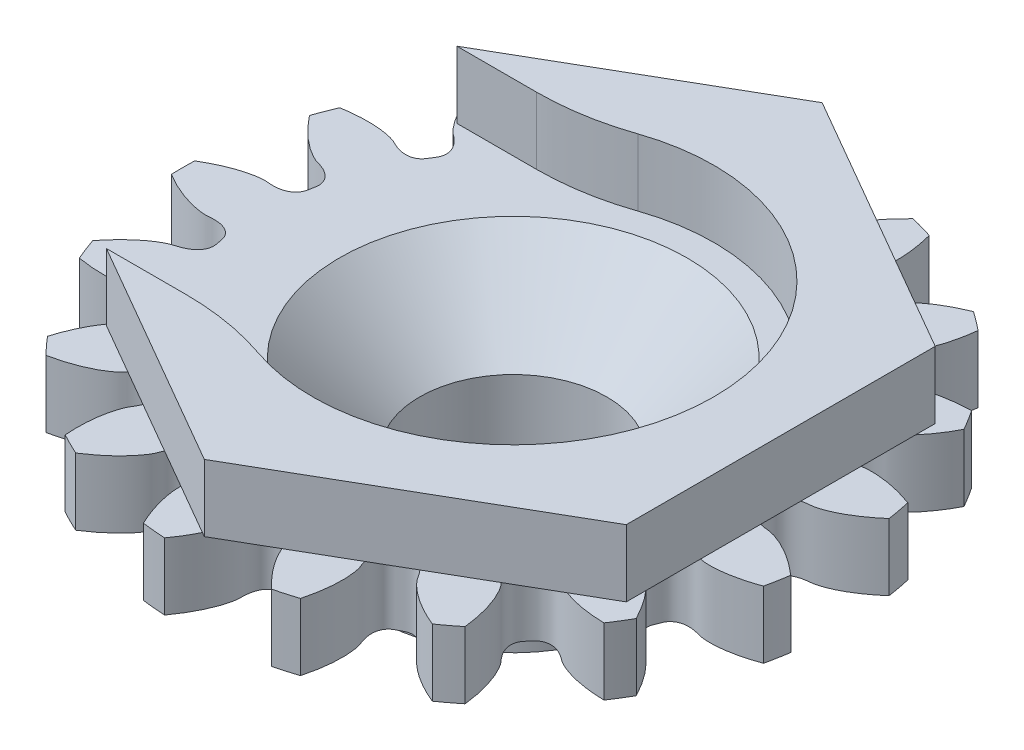
SolidWorks part; units mm, degrees
material "ABS"
ref_plane "前视基准面" through (0, 0, 0) normal (0, 0, 1) x (1, 0, 0)
ref_plane "上视基准面" through (0, 0, 0) normal (0, 1, 0) x (1, 0, 0)
ref_plane "右视基准面" through (0, 0, 0) normal (1, 0, 0) x (0, 0, -1)
sketch "草图1" plane through (0, 0, 0) normal (0, 1, 0) x (1, 0, 0)
  arc A0 (14.1766, -20.2266) -> (15.5749, -19.1706) centre (0, 0) ccw
  arc A1 (20.5259, -13.7396) -> (21.4484, -12.2498) centre (0, 0) ccw
  arc A2 (24.1032, -5.397) -> (24.4251, -3.6746) centre (0, 0) ccw
  arc A3 (24.4251, 3.6746) -> (24.1032, 5.397) centre (0, 0) ccw
  arc A4 (21.4484, 12.2498) -> (20.5259, 13.7396) centre (0, 0) ccw
  arc A5 (15.5749, 19.1706) -> (14.1766, 20.2266) centre (0, 0) ccw
  arc A6 (7.5979, 23.5024) -> (5.9126, 23.9819) centre (0, 0) ccw
  arc A7 (-1.4052, 24.66) -> (-3.15, 24.4983) centre (0, 0) ccw
  arc A8 (-10.2185, 22.4871) -> (-11.7871, 21.7061) centre (0, 0) ccw
  arc A9 (-17.6518, 17.2773) -> (-18.8323, 15.9824) centre (0, 0) ccw
  arc A10 (-22.7011, 9.734) -> (-23.3341, 8.1001) centre (0, 0) ccw
  arc A11 (-24.6845, 0.8761) -> (-24.6845, -0.8761) centre (0, 0) ccw
  arc A12 (-23.3341, -8.1001) -> (-22.7011, -9.734) centre (0, 0) ccw
  arc A13 (-18.8323, -15.9824) -> (-17.6518, -17.2773) centre (0, 0) ccw
  arc A14 (-11.7871, -21.7061) -> (-10.2185, -22.4871) centre (0, 0) ccw
  arc A15 (-3.15, -24.4983) -> (-1.4052, -24.66) centre (0, 0) ccw
  arc A16 (5.9126, -23.9819) -> (7.5979, -23.5024) centre (0, 0) ccw
  spline S0 degree 3 poles (7.5979, -23.5024) (7.6571, -23.2793) (7.7407, -22.9281) (7.8317, -22.4531) (7.8892, -22.0896) (7.9319, -21.7465) (7.9614, -21.4245) (7.979, -21.1239) (7.9861, -20.8452) (7.9844, -20.5887) (7.9751, -20.3547) (7.9598, -20.1434) (7.9399, -19.9548) (7.9169, -19.7891) (7.8924, -19.6462) (7.8677, -19.5261) (7.8443, -19.4285) (7.8237, -19.3532) (7.7717, -19.1857) (7.6897, -19.0075) (7.6268, -18.795) (7.5931, -18.6651) (7.5663, -18.537) (7.5463, -18.4107) (7.5333, -18.2857) (7.5277, -18.1616) (7.5302, -18.0377) (7.5415, -17.9135) (7.5631, -17.7881) (7.597, -17.6612) (7.6456, -17.5329) (7.7122, -17.4041) (7.7999, -17.2778) (7.9111, -17.1586) (8.0352, -17.0633) (8.2001, -16.9672) (8.4041, -16.8777) (8.5985, -16.7688) (8.7745, -16.6951) (8.9254, -16.6536) (9.0875, -16.6367) (9.2412, -16.6428) (9.384, -16.6673) (9.5158, -16.7058) (9.6374, -16.7552) (9.7505, -16.8135) (9.8565, -16.8794) (9.9568, -16.9521) (10.0525, -17.0313) (10.1444, -17.117) (10.2331, -17.2091) (10.3192, -17.3076) (10.4026, -17.4129) (10.5343, -17.5911) (10.627, -17.764) (10.7294, -17.9063) (10.777, -17.9681) (10.8408, -18.0456) (10.9218, -18.1378) (11.021, -18.2435) (11.1394, -18.3616) (11.2779, -18.4911) (11.4373, -18.6307) (11.6185, -18.7791) (11.8221, -18.9351) (12.0488, -19.0973) (12.2993, -19.2644) (12.5741, -19.435) (12.8736, -19.6076) (13.1983, -19.7809) (13.6322, -19.9944) (13.9629, -20.1394) (14.1766, -20.2266) knots 0.010677 0.010677 0.010677 0.010677 0.058365 0.085243 0.110586 0.134392 0.156663 0.177398 0.196597 0.21426 0.230387 0.244978 0.258033 0.269552 0.279536 0.287983 0.294895 0.300271 0.30411 0.331114 0.340625 0.349862 0.358855 0.367643 0.376273 0.384801 0.3933 0.401854 0.410565 0.419553 0.428946 0.438871 0.449424 0.460632 0.472413 0.481614 0.5 0.518386 0.527587 0.539368 0.550576 0.561129 0.571054 0.580447 0.589435 0.598146 0.6067 0.615199 0.623727 0.632357 0.641145 0.650138 0.659375 0.668886 0.69589 0.699729 0.705105 0.712017 0.720464 0.730448 0.741967 0.755022 0.769613 0.78574 0.803403 0.822602 0.843337 0.865608 0.889414 0.914757 0.941635 0.989323 0.989323 0.989323 0.989323
  spline S1 degree 3 poles (15.5749, -19.1706) (15.5495, -18.9412) (15.5005, -18.5835) (15.4139, -18.1078) (15.3361, -17.7481) (15.252, -17.4127) (15.1632, -17.1018) (15.071, -16.8151) (14.977, -16.5526) (14.8827, -16.3141) (14.7895, -16.0992) (14.6989, -15.9077) (14.6122, -15.7391) (14.531, -15.5929) (14.4565, -15.4685) (14.39, -15.3654) (14.3329, -15.2828) (14.2865, -15.2201) (14.1776, -15.0827) (14.0367, -14.9461) (13.9014, -14.7707) (13.8229, -14.6617) (13.7517, -14.552) (13.6874, -14.4414) (13.6302, -14.3296) (13.5801, -14.2159) (13.5377, -14.0995) (13.5033, -13.9795) (13.4782, -13.8548) (13.464, -13.7243) (13.4629, -13.587) (13.4785, -13.4429) (13.5147, -13.2934) (13.5753, -13.1421) (13.6566, -13.0084) (13.7756, -12.8592) (13.9335, -12.7021) (14.0754, -12.5303) (14.2129, -12.398) (14.3386, -12.3048) (14.4837, -12.2305) (14.6292, -12.1806) (14.7712, -12.1519) (14.908, -12.1402) (15.0393, -12.1424) (15.1658, -12.1559) (15.2884, -12.179) (15.4082, -12.2105) (15.5261, -12.2499) (15.6428, -12.2965) (15.7588, -12.3504) (15.8746, -12.4111) (15.9904, -12.4792) (16.1775, -12.5978) (16.3265, -12.7255) (16.4733, -12.8213) (16.5401, -12.8617) (16.6276, -12.9109) (16.7364, -12.9675) (16.8671, -13.0303) (17.0202, -13.0977) (17.1961, -13.1684) (17.3952, -13.241) (17.6177, -13.3139) (17.8639, -13.3858) (18.134, -13.4552) (18.4279, -13.5205) (18.7457, -13.5803) (19.0874, -13.6331) (19.4527, -13.6773) (19.9345, -13.7197) (20.2952, -13.7355) (20.5259, -13.7396) knots 0.010677 0.010677 0.010677 0.010677 0.058365 0.085243 0.110586 0.134392 0.156663 0.177398 0.196597 0.21426 0.230387 0.244978 0.258033 0.269552 0.279536 0.287983 0.294895 0.300271 0.30411 0.331114 0.340625 0.349862 0.358855 0.367643 0.376273 0.384801 0.3933 0.401854 0.410565 0.419553 0.428946 0.438871 0.449424 0.460632 0.472413 0.481614 0.5 0.518386 0.527587 0.539368 0.550576 0.561129 0.571054 0.580447 0.589435 0.598146 0.6067 0.615199 0.623727 0.632357 0.641145 0.650138 0.659375 0.668886 0.69589 0.699729 0.705105 0.712017 0.720464 0.730448 0.741967 0.755022 0.769613 0.78574 0.803403 0.822602 0.843337 0.865608 0.889414 0.914757 0.941635 0.989323 0.989323 0.989323 0.989323
  spline S2 degree 3 poles (21.4484, -12.2498) (21.3418, -12.0451) (21.167, -11.7292) (20.9143, -11.3169) (20.7118, -11.0095) (20.5123, -10.7272) (20.3171, -10.4693) (20.1276, -10.2354) (19.9451, -10.0245) (19.771, -9.8362) (19.6065, -9.6695) (19.4528, -9.5237) (19.3111, -9.3977) (19.1825, -9.2907) (19.0681, -9.2017) (18.9689, -9.1295) (18.8859, -9.0732) (18.8199, -9.0314) (18.6687, -8.9426) (18.488, -8.8662) (18.2984, -8.7515) (18.1859, -8.6782) (18.0799, -8.6016) (17.98, -8.5218) (17.8862, -8.4382) (17.7985, -8.3502) (17.7168, -8.257) (17.6415, -8.1575) (17.573, -8.0503) (17.5125, -7.9337) (17.462, -7.8061) (17.4244, -7.6661) (17.4042, -7.5137) (17.4061, -7.3507) (17.4335, -7.1966) (17.4906, -7.0146) (17.5811, -6.811) (17.6514, -6.5996) (17.7319, -6.4265) (17.8154, -6.2942) (17.9238, -6.1725) (18.0415, -6.0734) (18.1635, -5.9953) (18.2868, -5.935) (18.4101, -5.8896) (18.5329, -5.8565) (18.6556, -5.8337) (18.7787, -5.8199) (18.9028, -5.814) (19.0285, -5.8154) (19.1561, -5.8237) (19.286, -5.8385) (19.4186, -5.8601) (19.6359, -5.9031) (19.821, -5.9683) (19.9925, -6.0046) (20.0694, -6.0182) (20.1687, -6.0325) (20.2906, -6.046) (20.4352, -6.0573) (20.6023, -6.0648) (20.7919, -6.0672) (21.0037, -6.063) (21.2376, -6.0506) (21.4931, -6.0287) (21.77, -5.9959) (22.0677, -5.9506) (22.3856, -5.8915) (22.7233, -5.8173) (23.08, -5.7266) (23.5445, -5.5921) (23.8865, -5.4765) (24.1032, -5.397) knots 0.010677 0.010677 0.010677 0.010677 0.058365 0.085243 0.110586 0.134392 0.156663 0.177398 0.196597 0.21426 0.230387 0.244978 0.258033 0.269552 0.279536 0.287983 0.294895 0.300271 0.30411 0.331114 0.340625 0.349862 0.358855 0.367643 0.376273 0.384801 0.3933 0.401854 0.410565 0.419553 0.428946 0.438871 0.449424 0.460632 0.472413 0.481614 0.5 0.518386 0.527587 0.539368 0.550576 0.561129 0.571054 0.580447 0.589435 0.598146 0.6067 0.615199 0.623727 0.632357 0.641145 0.650138 0.659375 0.668886 0.69589 0.699729 0.705105 0.712017 0.720464 0.730448 0.741967 0.755022 0.769613 0.78574 0.803403 0.822602 0.843337 0.865608 0.889414 0.914757 0.941635 0.989323 0.989323 0.989323 0.989323
  spline S3 degree 3 poles (24.4251, -3.6746) (24.2518, -3.5221) (23.9747, -3.2908) (23.5901, -2.9975) (23.2903, -2.7841) (23.0023, -2.5929) (22.7271, -2.423) (22.4659, -2.2733) (22.2196, -2.1426) (21.9892, -2.0299) (21.7756, -1.9339) (21.5796, -1.8534) (21.4019, -1.7871) (21.2434, -1.7338) (21.1045, -1.6921) (20.986, -1.6607) (20.8882, -1.6381) (20.8116, -1.623) (20.6385, -1.5948) (20.4424, -1.5889) (20.2242, -1.5504) (20.0928, -1.5227) (19.9662, -1.4896) (19.8443, -1.4512) (19.7266, -1.4071) (19.613, -1.3568) (19.5032, -1.2994) (19.397, -1.2338) (19.2944, -1.1586) (19.1959, -1.0717) (19.1027, -0.971) (19.0171, -0.854) (18.9432, -0.7192) (18.8861, -0.5665) (18.856, -0.4129) (18.8435, -0.2225) (18.8543, 0) (18.8435, 0.2225) (18.856, 0.4129) (18.8861, 0.5665) (18.9432, 0.7192) (19.0171, 0.854) (19.1027, 0.971) (19.1959, 1.0717) (19.2944, 1.1586) (19.397, 1.2338) (19.5032, 1.2994) (19.613, 1.3568) (19.7266, 1.4071) (19.8443, 1.4512) (19.9662, 1.4896) (20.0928, 1.5227) (20.2242, 1.5504) (20.4424, 1.5889) (20.6385, 1.5948) (20.8116, 1.623) (20.8882, 1.6381) (20.986, 1.6607) (21.1045, 1.6921) (21.2434, 1.7338) (21.4019, 1.7871) (21.5796, 1.8534) (21.7756, 1.9339) (21.9892, 2.0299) (22.2196, 2.1426) (22.4659, 2.2733) (22.7271, 2.423) (23.0023, 2.5929) (23.2903, 2.7841) (23.5901, 2.9975) (23.9747, 3.2908) (24.2518, 3.5221) (24.4251, 3.6746) knots 0.010677 0.010677 0.010677 0.010677 0.058365 0.085243 0.110586 0.134392 0.156663 0.177398 0.196597 0.21426 0.230387 0.244978 0.258033 0.269552 0.279536 0.287983 0.294895 0.300271 0.30411 0.331114 0.340625 0.349862 0.358855 0.367643 0.376273 0.384801 0.3933 0.401854 0.410565 0.419553 0.428946 0.438871 0.449424 0.460632 0.472413 0.481614 0.5 0.518386 0.527587 0.539368 0.550576 0.561129 0.571054 0.580447 0.589435 0.598146 0.6067 0.615199 0.623727 0.632357 0.641145 0.650138 0.659375 0.668886 0.69589 0.699729 0.705105 0.712017 0.720464 0.730448 0.741967 0.755022 0.769613 0.78574 0.803403 0.822602 0.843337 0.865608 0.889414 0.914757 0.941635 0.989323 0.989323 0.989323 0.989323
  spline S4 degree 3 poles (24.1032, 5.397) (23.8865, 5.4765) (23.5445, 5.5921) (23.08, 5.7266) (22.7233, 5.8173) (22.3856, 5.8915) (22.0677, 5.9506) (21.77, 5.9959) (21.4931, 6.0287) (21.2376, 6.0506) (21.0037, 6.063) (20.7919, 6.0672) (20.6023, 6.0648) (20.4352, 6.0573) (20.2906, 6.046) (20.1687, 6.0325) (20.0694, 6.0182) (19.9925, 6.0046) (19.821, 5.9683) (19.6359, 5.9031) (19.4186, 5.8601) (19.286, 5.8385) (19.1561, 5.8237) (19.0285, 5.8154) (18.9028, 5.814) (18.7787, 5.8199) (18.6556, 5.8337) (18.5329, 5.8565) (18.4101, 5.8896) (18.2868, 5.935) (18.1635, 5.9953) (18.0415, 6.0734) (17.9238, 6.1725) (17.8154, 6.2942) (17.7319, 6.4265) (17.6514, 6.5996) (17.5811, 6.811) (17.4906, 7.0146) (17.4335, 7.1966) (17.4061, 7.3507) (17.4042, 7.5137) (17.4244, 7.6661) (17.462, 7.8061) (17.5125, 7.9337) (17.573, 8.0503) (17.6415, 8.1575) (17.7168, 8.257) (17.7985, 8.3502) (17.8862, 8.4382) (17.98, 8.5218) (18.0799, 8.6016) (18.1859, 8.6782) (18.2984, 8.7515) (18.488, 8.8662) (18.6687, 8.9426) (18.8199, 9.0314) (18.8859, 9.0732) (18.9689, 9.1295) (19.0681, 9.2017) (19.1825, 9.2907) (19.3111, 9.3977) (19.4528, 9.5237) (19.6065, 9.6695) (19.771, 9.8362) (19.9451, 10.0245) (20.1276, 10.2354) (20.3171, 10.4693) (20.5123, 10.7272) (20.7118, 11.0095) (20.9143, 11.3169) (21.167, 11.7292) (21.3418, 12.0451) (21.4484, 12.2498) knots 0.010677 0.010677 0.010677 0.010677 0.058365 0.085243 0.110586 0.134392 0.156663 0.177398 0.196597 0.21426 0.230387 0.244978 0.258033 0.269552 0.279536 0.287983 0.294895 0.300271 0.30411 0.331114 0.340625 0.349862 0.358855 0.367643 0.376273 0.384801 0.3933 0.401854 0.410565 0.419553 0.428946 0.438871 0.449424 0.460632 0.472413 0.481614 0.5 0.518386 0.527587 0.539368 0.550576 0.561129 0.571054 0.580447 0.589435 0.598146 0.6067 0.615199 0.623727 0.632357 0.641145 0.650138 0.659375 0.668886 0.69589 0.699729 0.705105 0.712017 0.720464 0.730448 0.741967 0.755022 0.769613 0.78574 0.803403 0.822602 0.843337 0.865608 0.889414 0.914757 0.941635 0.989323 0.989323 0.989323 0.989323
  spline S5 degree 3 poles (20.5259, 13.7396) (20.2952, 13.7355) (19.9345, 13.7197) (19.4527, 13.6773) (19.0874, 13.6331) (18.7457, 13.5803) (18.4279, 13.5205) (18.134, 13.4552) (17.8639, 13.3858) (17.6177, 13.3139) (17.3952, 13.241) (17.1961, 13.1684) (17.0202, 13.0977) (16.8671, 13.0303) (16.7364, 12.9675) (16.6276, 12.9109) (16.5401, 12.8617) (16.4733, 12.8213) (16.3265, 12.7255) (16.1775, 12.5978) (15.9904, 12.4792) (15.8746, 12.4111) (15.7588, 12.3504) (15.6428, 12.2965) (15.5261, 12.2499) (15.4082, 12.2105) (15.2884, 12.179) (15.1658, 12.1559) (15.0393, 12.1424) (14.908, 12.1402) (14.7712, 12.1519) (14.6292, 12.1806) (14.4837, 12.2305) (14.3386, 12.3048) (14.2129, 12.398) (14.0754, 12.5303) (13.9335, 12.7021) (13.7756, 12.8592) (13.6566, 13.0084) (13.5753, 13.1421) (13.5147, 13.2934) (13.4785, 13.4429) (13.4629, 13.587) (13.464, 13.7243) (13.4782, 13.8548) (13.5033, 13.9795) (13.5377, 14.0995) (13.5801, 14.2159) (13.6302, 14.3296) (13.6874, 14.4414) (13.7517, 14.552) (13.8229, 14.6617) (13.9014, 14.7707) (14.0367, 14.9461) (14.1776, 15.0827) (14.2865, 15.2201) (14.3329, 15.2828) (14.39, 15.3654) (14.4565, 15.4685) (14.531, 15.5929) (14.6122, 15.7391) (14.6989, 15.9077) (14.7895, 16.0992) (14.8827, 16.3141) (14.977, 16.5526) (15.071, 16.8151) (15.1632, 17.1018) (15.252, 17.4127) (15.3361, 17.7481) (15.4139, 18.1078) (15.5005, 18.5835) (15.5495, 18.9412) (15.5749, 19.1706) knots 0.010677 0.010677 0.010677 0.010677 0.058365 0.085243 0.110586 0.134392 0.156663 0.177398 0.196597 0.21426 0.230387 0.244978 0.258033 0.269552 0.279536 0.287983 0.294895 0.300271 0.30411 0.331114 0.340625 0.349862 0.358855 0.367643 0.376273 0.384801 0.3933 0.401854 0.410565 0.419553 0.428946 0.438871 0.449424 0.460632 0.472413 0.481614 0.5 0.518386 0.527587 0.539368 0.550576 0.561129 0.571054 0.580447 0.589435 0.598146 0.6067 0.615199 0.623727 0.632357 0.641145 0.650138 0.659375 0.668886 0.69589 0.699729 0.705105 0.712017 0.720464 0.730448 0.741967 0.755022 0.769613 0.78574 0.803403 0.822602 0.843337 0.865608 0.889414 0.914757 0.941635 0.989323 0.989323 0.989323 0.989323
  spline S6 degree 3 poles (14.1766, 20.2266) (13.9629, 20.1394) (13.6322, 19.9944) (13.1983, 19.7809) (12.8736, 19.6076) (12.5741, 19.435) (12.2993, 19.2644) (12.0488, 19.0973) (11.8221, 18.9351) (11.6185, 18.7791) (11.4373, 18.6307) (11.2779, 18.4911) (11.1394, 18.3616) (11.021, 18.2435) (10.9218, 18.1378) (10.8408, 18.0456) (10.777, 17.9681) (10.7294, 17.9063) (10.627, 17.764) (10.5343, 17.5911) (10.4026, 17.4129) (10.3192, 17.3076) (10.2331, 17.2091) (10.1444, 17.117) (10.0525, 17.0313) (9.9568, 16.9521) (9.8565, 16.8794) (9.7505, 16.8135) (9.6374, 16.7552) (9.5158, 16.7058) (9.384, 16.6673) (9.2412, 16.6428) (9.0875, 16.6367) (8.9254, 16.6536) (8.7745, 16.6951) (8.5985, 16.7688) (8.4041, 16.8777) (8.2001, 16.9672) (8.0352, 17.0633) (7.9111, 17.1586) (7.7999, 17.2778) (7.7122, 17.4041) (7.6456, 17.5329) (7.597, 17.6612) (7.5631, 17.7881) (7.5415, 17.9135) (7.5302, 18.0377) (7.5277, 18.1616) (7.5333, 18.2857) (7.5463, 18.4107) (7.5663, 18.537) (7.5931, 18.6651) (7.6268, 18.795) (7.6897, 19.0075) (7.7717, 19.1857) (7.8237, 19.3532) (7.8443, 19.4285) (7.8677, 19.5261) (7.8924, 19.6462) (7.9169, 19.7891) (7.9399, 19.9548) (7.9598, 20.1434) (7.9751, 20.3547) (7.9844, 20.5887) (7.9861, 20.8452) (7.979, 21.1239) (7.9614, 21.4245) (7.9319, 21.7465) (7.8892, 22.0896) (7.8317, 22.4531) (7.7407, 22.9281) (7.6571, 23.2793) (7.5979, 23.5024) knots 0.010677 0.010677 0.010677 0.010677 0.058365 0.085243 0.110586 0.134392 0.156663 0.177398 0.196597 0.21426 0.230387 0.244978 0.258033 0.269552 0.279536 0.287983 0.294895 0.300271 0.30411 0.331114 0.340625 0.349862 0.358855 0.367643 0.376273 0.384801 0.3933 0.401854 0.410565 0.419553 0.428946 0.438871 0.449424 0.460632 0.472413 0.481614 0.5 0.518386 0.527587 0.539368 0.550576 0.561129 0.571054 0.580447 0.589435 0.598146 0.6067 0.615199 0.623727 0.632357 0.641145 0.650138 0.659375 0.668886 0.69589 0.699729 0.705105 0.712017 0.720464 0.730448 0.741967 0.755022 0.769613 0.78574 0.803403 0.822602 0.843337 0.865608 0.889414 0.914757 0.941635 0.989323 0.989323 0.989323 0.989323
  spline S7 degree 3 poles (5.9126, 23.9819) (5.7448, 23.8234) (5.4888, 23.5688) (5.1614, 23.2129) (4.9212, 22.9341) (4.7042, 22.6649) (4.5097, 22.4066) (4.3364, 22.1603) (4.1836, 21.9271) (4.0501, 21.7081) (3.9348, 21.5042) (3.8366, 21.3165) (3.7542, 21.1457) (3.6865, 20.9928) (3.6322, 20.8584) (3.5899, 20.7432) (3.5584, 20.6479) (3.5363, 20.573) (3.4923, 20.4033) (3.4683, 20.2086) (3.4098, 19.9949) (3.3701, 19.8666) (3.3255, 19.7436) (3.276, 19.6257) (3.2212, 19.5126) (3.1606, 19.4042) (3.0934, 19.3001) (3.0183, 19.2004) (2.9339, 19.1052) (2.8383, 19.0152) (2.7294, 18.9317) (2.6051, 18.8572) (2.464, 18.796) (2.3067, 18.7532) (2.151, 18.7375) (1.9602, 18.7426) (1.7397, 18.7739) (1.5171, 18.7836) (1.3286, 18.8137) (1.1785, 18.8578) (1.0318, 18.9287) (0.9043, 19.0148) (0.7957, 19.1108) (0.704, 19.2129) (0.6266, 19.319) (0.5612, 19.4281) (0.5057, 19.5399) (0.4587, 19.6545) (0.419, 19.7723) (0.386, 19.8935) (0.359, 20.0185) (0.3377, 20.1476) (0.3223, 20.281) (0.3041, 20.5018) (0.3162, 20.6976) (0.3042, 20.8725) (0.2962, 20.9502) (0.2828, 21.0497) (0.2624, 21.1706) (0.2337, 21.3127) (0.1952, 21.4755) (0.1456, 21.6585) (0.0836, 21.8611) (0.0077, 22.0827) (-0.0833, 22.3225) (-0.1907, 22.5798) (-0.3157, 22.8537) (-0.4595, 23.1434) (-0.6233, 23.4478) (-0.8081, 23.766) (-1.0646, 24.176) (-1.2694, 24.4734) (-1.4052, 24.66) knots 0.010677 0.010677 0.010677 0.010677 0.058365 0.085243 0.110586 0.134392 0.156663 0.177398 0.196597 0.21426 0.230387 0.244978 0.258033 0.269552 0.279536 0.287983 0.294895 0.300271 0.30411 0.331114 0.340625 0.349862 0.358855 0.367643 0.376273 0.384801 0.3933 0.401854 0.410565 0.419553 0.428946 0.438871 0.449424 0.460632 0.472413 0.481614 0.5 0.518386 0.527587 0.539368 0.550576 0.561129 0.571054 0.580447 0.589435 0.598146 0.6067 0.615199 0.623727 0.632357 0.641145 0.650138 0.659375 0.668886 0.69589 0.699729 0.705105 0.712017 0.720464 0.730448 0.741967 0.755022 0.769613 0.78574 0.803403 0.822602 0.843337 0.865608 0.889414 0.914757 0.941635 0.989323 0.989323 0.989323 0.989323
  spline S8 degree 3 poles (-3.15, 24.4983) (-3.2492, 24.2899) (-3.3958, 23.96) (-3.5726, 23.5099) (-3.6959, 23.1631) (-3.8009, 22.8338) (-3.8891, 22.5226) (-3.9616, 22.2303) (-4.0199, 21.9577) (-4.0653, 21.7053) (-4.0991, 21.4735) (-4.1229, 21.263) (-4.138, 21.074) (-4.1459, 20.9069) (-4.148, 20.7619) (-4.1458, 20.6393) (-4.1407, 20.5391) (-4.1343, 20.4613) (-4.114, 20.2871) (-4.0661, 20.0969) (-4.0434, 19.8764) (-4.0341, 19.7425) (-4.0313, 19.6117) (-4.0348, 19.4839) (-4.0451, 19.3586) (-4.0624, 19.2356) (-4.0875, 19.1143) (-4.1215, 18.9942) (-4.1658, 18.875) (-4.2224, 18.7565) (-4.2938, 18.6392) (-4.3829, 18.5249) (-4.4923, 18.4169) (-4.6235, 18.3201) (-4.763, 18.2492) (-4.9427, 18.1851) (-5.1597, 18.1346) (-5.3708, 18.0633) (-5.5574, 18.0232) (-5.7133, 18.0101) (-5.8758, 18.0232) (-6.0257, 18.0575) (-6.1616, 18.1078) (-6.284, 18.1699) (-6.3945, 18.2408) (-6.495, 18.3189) (-6.5871, 18.4031) (-6.6723, 18.493) (-6.7518, 18.5885) (-6.8264, 18.6896) (-6.8967, 18.7964) (-6.9632, 18.9091) (-7.0258, 19.0279) (-7.1225, 19.2272) (-7.1819, 19.4142) (-7.2564, 19.5729) (-7.2919, 19.6425) (-7.3403, 19.7304) (-7.403, 19.8358) (-7.4811, 19.9579) (-7.5758, 20.0959) (-7.6881, 20.2486) (-7.8192, 20.4151) (-7.97, 20.5943) (-8.1415, 20.785) (-8.3345, 20.9861) (-8.5501, 21.1964) (-8.7888, 21.4146) (-9.0515, 21.6393) (-9.3388, 21.8692) (-9.7261, 22.1589) (-10.0245, 22.3622) (-10.2185, 22.4871) knots 0.010677 0.010677 0.010677 0.010677 0.058365 0.085243 0.110586 0.134392 0.156663 0.177398 0.196597 0.21426 0.230387 0.244978 0.258033 0.269552 0.279536 0.287983 0.294895 0.300271 0.30411 0.331114 0.340625 0.349862 0.358855 0.367643 0.376273 0.384801 0.3933 0.401854 0.410565 0.419553 0.428946 0.438871 0.449424 0.460632 0.472413 0.481614 0.5 0.518386 0.527587 0.539368 0.550576 0.561129 0.571054 0.580447 0.589435 0.598146 0.6067 0.615199 0.623727 0.632357 0.641145 0.650138 0.659375 0.668886 0.69589 0.699729 0.705105 0.712017 0.720464 0.730448 0.741967 0.755022 0.769613 0.78574 0.803403 0.822602 0.843337 0.865608 0.889414 0.914757 0.941635 0.989323 0.989323 0.989323 0.989323
  spline S9 degree 3 poles (-11.7871, 21.7061) (-11.8043, 21.4759) (-11.8219, 21.1153) (-11.8241, 20.6317) (-11.8138, 20.2639) (-11.7928, 19.9188) (-11.7625, 19.5968) (-11.7246, 19.2981) (-11.6805, 19.0228) (-11.6316, 18.771) (-11.5795, 18.5427) (-11.5256, 18.3378) (-11.4714, 18.1561) (-11.4184, 17.9974) (-11.368, 17.8615) (-11.3216, 17.7479) (-11.2807, 17.6563) (-11.2466, 17.5861) (-11.1648, 17.431) (-11.0514, 17.2709) (-10.9505, 17.0736) (-10.8935, 16.952) (-10.8436, 16.8311) (-10.8008, 16.7106) (-10.765, 16.5902) (-10.7368, 16.4692) (-10.7164, 16.347) (-10.7047, 16.2227) (-10.7029, 16.0955) (-10.7129, 15.9646) (-10.7371, 15.8295) (-10.7789, 15.6907) (-10.8419, 15.5504) (-10.9293, 15.4128) (-11.0337, 15.2963) (-11.1782, 15.1715) (-11.3623, 15.0461) (-11.5333, 14.9033) (-11.6928, 14.7986) (-11.8335, 14.73) (-11.9897, 14.6836) (-12.1419, 14.6613) (-12.2868, 14.6592) (-12.4234, 14.6728) (-12.5521, 14.6991) (-12.6739, 14.7356) (-12.7902, 14.7808) (-12.9022, 14.8339) (-13.0108, 14.8942) (-13.1169, 14.9615) (-13.2211, 15.0357) (-13.3238, 15.1168) (-13.425, 15.2049) (-13.5872, 15.3559) (-13.7102, 15.5088) (-13.8369, 15.6299) (-13.8952, 15.6819) (-13.9721, 15.7464) (-14.0686, 15.8221) (-14.1856, 15.9077) (-14.3237, 16.0021) (-14.4836, 16.104) (-14.666, 16.2119) (-14.8713, 16.3245) (-15.1001, 16.4404) (-15.3528, 16.5582) (-15.6297, 16.6764) (-15.9312, 16.7936) (-16.2573, 16.9083) (-16.6083, 17.0189) (-17.0741, 17.1491) (-17.4257, 17.2308) (-17.6518, 17.2773) knots 0.010677 0.010677 0.010677 0.010677 0.058365 0.085243 0.110586 0.134392 0.156663 0.177398 0.196597 0.21426 0.230387 0.244978 0.258033 0.269552 0.279536 0.287983 0.294895 0.300271 0.30411 0.331114 0.340625 0.349862 0.358855 0.367643 0.376273 0.384801 0.3933 0.401854 0.410565 0.419553 0.428946 0.438871 0.449424 0.460632 0.472413 0.481614 0.5 0.518386 0.527587 0.539368 0.550576 0.561129 0.571054 0.580447 0.589435 0.598146 0.6067 0.615199 0.623727 0.632357 0.641145 0.650138 0.659375 0.668886 0.69589 0.699729 0.705105 0.712017 0.720464 0.730448 0.741967 0.755022 0.769613 0.78574 0.803403 0.822602 0.843337 0.865608 0.889414 0.914757 0.941635 0.989323 0.989323 0.989323 0.989323
  spline S10 degree 3 poles (-18.8323, 15.9824) (-18.7652, 15.7615) (-18.6513, 15.4189) (-18.4787, 14.9671) (-18.3362, 14.6279) (-18.1919, 14.3137) (-18.0474, 14.0243) (-17.9041, 13.7595) (-17.7635, 13.5188) (-17.627, 13.3016) (-17.4959, 13.1076) (-17.3716, 12.9359) (-17.2555, 12.7861) (-17.1488, 12.6573) (-17.0527, 12.5488) (-16.9684, 12.4596) (-16.8971, 12.3889) (-16.84, 12.3358) (-16.7076, 12.2207) (-16.5441, 12.1124) (-16.3788, 11.9648) (-16.2816, 11.8721) (-16.1915, 11.7773) (-16.108, 11.6805) (-16.0312, 11.5811) (-15.9611, 11.4785) (-15.8979, 11.3719) (-15.8421, 11.2602) (-15.7945, 11.1423) (-15.7565, 11.0166) (-15.7303, 10.8818) (-15.7191, 10.7374) (-15.7272, 10.5837) (-15.759, 10.4239) (-15.8143, 10.2775) (-15.9039, 10.109) (-16.0303, 9.9255) (-16.1382, 9.7306) (-16.2491, 9.5753) (-16.3555, 9.4606) (-16.4844, 9.3609) (-16.6183, 9.2851) (-16.7526, 9.2307) (-16.8849, 9.1942) (-17.0144, 9.1722) (-17.1412, 9.1622) (-17.266, 9.1624) (-17.3896, 9.1714) (-17.5127, 9.1884) (-17.6359, 9.2128) (-17.7598, 9.2444) (-17.8848, 9.2829) (-18.0111, 9.3285) (-18.2169, 9.4107) (-18.3868, 9.5088) (-18.5487, 9.576) (-18.6218, 9.6034) (-18.7168, 9.6358) (-18.8342, 9.6714) (-18.9742, 9.7091) (-19.1371, 9.7472) (-19.323, 9.7844) (-19.532, 9.8192) (-19.7642, 9.85) (-20.0194, 9.8754) (-20.2976, 9.894) (-20.5985, 9.9042) (-20.9219, 9.9046) (-21.2675, 9.8937) (-21.6347, 9.87) (-22.116, 9.8232) (-22.4735, 9.7724) (-22.7011, 9.734) knots 0.010677 0.010677 0.010677 0.010677 0.058365 0.085243 0.110586 0.134392 0.156663 0.177398 0.196597 0.21426 0.230387 0.244978 0.258033 0.269552 0.279536 0.287983 0.294895 0.300271 0.30411 0.331114 0.340625 0.349862 0.358855 0.367643 0.376273 0.384801 0.3933 0.401854 0.410565 0.419553 0.428946 0.438871 0.449424 0.460632 0.472413 0.481614 0.5 0.518386 0.527587 0.539368 0.550576 0.561129 0.571054 0.580447 0.589435 0.598146 0.6067 0.615199 0.623727 0.632357 0.641145 0.650138 0.659375 0.668886 0.69589 0.699729 0.705105 0.712017 0.720464 0.730448 0.741967 0.755022 0.769613 0.78574 0.803403 0.822602 0.843337 0.865608 0.889414 0.914757 0.941635 0.989323 0.989323 0.989323 0.989323
  spline S11 degree 3 poles (-23.3341, 8.1001) (-23.1917, 7.9184) (-22.9618, 7.6401) (-22.6376, 7.2812) (-22.3822, 7.0163) (-22.1342, 6.7754) (-21.8949, 6.5578) (-21.6656, 6.3626) (-21.4475, 6.1889) (-21.2418, 6.0358) (-21.0495, 5.9022) (-20.8716, 5.787) (-20.7091, 5.6893) (-20.5631, 5.6077) (-20.4343, 5.5412) (-20.3235, 5.4885) (-20.2315, 5.4484) (-20.159, 5.4195) (-19.994, 5.36) (-19.8024, 5.3181) (-19.5949, 5.2402) (-19.4709, 5.1888) (-19.3526, 5.133) (-19.2397, 5.0729) (-19.1322, 5.0079) (-19.0298, 4.9376) (-18.9324, 4.861) (-18.84, 4.777) (-18.753, 4.6842) (-18.6722, 4.5807) (-18.5991, 4.4646) (-18.5364, 4.3339) (-18.4885, 4.1877) (-18.4604, 4.0272) (-18.4591, 3.8707) (-18.4818, 3.6812) (-18.5333, 3.4645) (-18.5635, 3.2437) (-18.6108, 3.0589) (-18.6686, 2.9134) (-18.7528, 2.7739) (-18.8503, 2.6549) (-18.9559, 2.5557) (-19.066, 2.4738) (-19.1788, 2.4065) (-19.2935, 2.3514) (-19.4099, 2.3064) (-19.5284, 2.2702) (-19.6493, 2.2416) (-19.773, 2.2199) (-19.9, 2.2046) (-20.0305, 2.1953) (-20.1647, 2.1922) (-20.3863, 2.1945) (-20.5801, 2.2246) (-20.7554, 2.2288) (-20.8335, 2.228) (-20.9338, 2.2238) (-21.0561, 2.2147) (-21.2003, 2.1992) (-21.3659, 2.1759) (-21.5527, 2.1434) (-21.7601, 2.1003) (-21.9878, 2.0452) (-22.2349, 1.9767) (-22.501, 1.8935) (-22.7853, 1.7944) (-23.0871, 1.6779) (-23.4053, 1.5429) (-23.7392, 1.3882) (-24.1711, 1.1706) (-24.4861, 0.9941) (-24.6845, 0.8761) knots 0.010677 0.010677 0.010677 0.010677 0.058365 0.085243 0.110586 0.134392 0.156663 0.177398 0.196597 0.21426 0.230387 0.244978 0.258033 0.269552 0.279536 0.287983 0.294895 0.300271 0.30411 0.331114 0.340625 0.349862 0.358855 0.367643 0.376273 0.384801 0.3933 0.401854 0.410565 0.419553 0.428946 0.438871 0.449424 0.460632 0.472413 0.481614 0.5 0.518386 0.527587 0.539368 0.550576 0.561129 0.571054 0.580447 0.589435 0.598146 0.6067 0.615199 0.623727 0.632357 0.641145 0.650138 0.659375 0.668886 0.69589 0.699729 0.705105 0.712017 0.720464 0.730448 0.741967 0.755022 0.769613 0.78574 0.803403 0.822602 0.843337 0.865608 0.889414 0.914757 0.941635 0.989323 0.989323 0.989323 0.989323
  spline S12 degree 3 poles (-24.6845, -0.8761) (-24.4861, -0.9941) (-24.1711, -1.1706) (-23.7392, -1.3882) (-23.4053, -1.5429) (-23.0871, -1.6779) (-22.7853, -1.7944) (-22.501, -1.8935) (-22.2349, -1.9767) (-21.9878, -2.0452) (-21.7601, -2.1003) (-21.5527, -2.1434) (-21.3659, -2.1759) (-21.2003, -2.1992) (-21.0561, -2.2147) (-20.9338, -2.2238) (-20.8335, -2.228) (-20.7554, -2.2288) (-20.5801, -2.2246) (-20.3863, -2.1945) (-20.1647, -2.1922) (-20.0305, -2.1953) (-19.9, -2.2046) (-19.773, -2.2199) (-19.6493, -2.2416) (-19.5284, -2.2702) (-19.4099, -2.3064) (-19.2935, -2.3514) (-19.1788, -2.4065) (-19.066, -2.4738) (-18.9559, -2.5557) (-18.8503, -2.6549) (-18.7528, -2.7739) (-18.6686, -2.9134) (-18.6108, -3.0589) (-18.5635, -3.2437) (-18.5333, -3.4645) (-18.4818, -3.6812) (-18.4591, -3.8707) (-18.4604, -4.0272) (-18.4885, -4.1877) (-18.5364, -4.3339) (-18.5991, -4.4646) (-18.6722, -4.5807) (-18.753, -4.6842) (-18.84, -4.777) (-18.9324, -4.861) (-19.0298, -4.9376) (-19.1322, -5.0079) (-19.2397, -5.0729) (-19.3526, -5.133) (-19.4709, -5.1888) (-19.5949, -5.2402) (-19.8024, -5.3181) (-19.994, -5.36) (-20.159, -5.4195) (-20.2315, -5.4484) (-20.3235, -5.4885) (-20.4343, -5.5412) (-20.5631, -5.6077) (-20.7091, -5.6893) (-20.8716, -5.787) (-21.0495, -5.9022) (-21.2418, -6.0358) (-21.4475, -6.1889) (-21.6656, -6.3626) (-21.8949, -6.5578) (-22.1342, -6.7754) (-22.3822, -7.0163) (-22.6376, -7.2812) (-22.9618, -7.6401) (-23.1917, -7.9184) (-23.3341, -8.1001) knots 0.010677 0.010677 0.010677 0.010677 0.058365 0.085243 0.110586 0.134392 0.156663 0.177398 0.196597 0.21426 0.230387 0.244978 0.258033 0.269552 0.279536 0.287983 0.294895 0.300271 0.30411 0.331114 0.340625 0.349862 0.358855 0.367643 0.376273 0.384801 0.3933 0.401854 0.410565 0.419553 0.428946 0.438871 0.449424 0.460632 0.472413 0.481614 0.5 0.518386 0.527587 0.539368 0.550576 0.561129 0.571054 0.580447 0.589435 0.598146 0.6067 0.615199 0.623727 0.632357 0.641145 0.650138 0.659375 0.668886 0.69589 0.699729 0.705105 0.712017 0.720464 0.730448 0.741967 0.755022 0.769613 0.78574 0.803403 0.822602 0.843337 0.865608 0.889414 0.914757 0.941635 0.989323 0.989323 0.989323 0.989323
  spline S13 degree 3 poles (-22.7011, -9.734) (-22.4735, -9.7724) (-22.116, -9.8232) (-21.6347, -9.87) (-21.2675, -9.8937) (-20.9219, -9.9046) (-20.5985, -9.9042) (-20.2976, -9.894) (-20.0194, -9.8754) (-19.7642, -9.85) (-19.532, -9.8192) (-19.323, -9.7844) (-19.1371, -9.7472) (-18.9742, -9.7091) (-18.8342, -9.6714) (-18.7168, -9.6358) (-18.6218, -9.6034) (-18.5487, -9.576) (-18.3868, -9.5088) (-18.2169, -9.4107) (-18.0111, -9.3285) (-17.8848, -9.2829) (-17.7598, -9.2444) (-17.6359, -9.2128) (-17.5127, -9.1884) (-17.3896, -9.1714) (-17.266, -9.1624) (-17.1412, -9.1622) (-17.0144, -9.1722) (-16.8849, -9.1942) (-16.7526, -9.2307) (-16.6183, -9.2851) (-16.4844, -9.3609) (-16.3555, -9.4606) (-16.2491, -9.5753) (-16.1382, -9.7306) (-16.0303, -9.9255) (-15.9039, -10.109) (-15.8143, -10.2775) (-15.759, -10.4239) (-15.7272, -10.5837) (-15.7191, -10.7374) (-15.7303, -10.8818) (-15.7565, -11.0166) (-15.7945, -11.1423) (-15.8421, -11.2602) (-15.8979, -11.3719) (-15.9611, -11.4785) (-16.0312, -11.5811) (-16.108, -11.6805) (-16.1915, -11.7773) (-16.2816, -11.8721) (-16.3788, -11.9648) (-16.5441, -12.1124) (-16.7076, -12.2207) (-16.84, -12.3358) (-16.8971, -12.3889) (-16.9684, -12.4596) (-17.0527, -12.5488) (-17.1488, -12.6573) (-17.2555, -12.7861) (-17.3716, -12.9359) (-17.4959, -13.1076) (-17.627, -13.3016) (-17.7635, -13.5188) (-17.9041, -13.7595) (-18.0474, -14.0243) (-18.1919, -14.3137) (-18.3362, -14.6279) (-18.4787, -14.9671) (-18.6513, -15.4189) (-18.7652, -15.7615) (-18.8323, -15.9824) knots 0.010677 0.010677 0.010677 0.010677 0.058365 0.085243 0.110586 0.134392 0.156663 0.177398 0.196597 0.21426 0.230387 0.244978 0.258033 0.269552 0.279536 0.287983 0.294895 0.300271 0.30411 0.331114 0.340625 0.349862 0.358855 0.367643 0.376273 0.384801 0.3933 0.401854 0.410565 0.419553 0.428946 0.438871 0.449424 0.460632 0.472413 0.481614 0.5 0.518386 0.527587 0.539368 0.550576 0.561129 0.571054 0.580447 0.589435 0.598146 0.6067 0.615199 0.623727 0.632357 0.641145 0.650138 0.659375 0.668886 0.69589 0.699729 0.705105 0.712017 0.720464 0.730448 0.741967 0.755022 0.769613 0.78574 0.803403 0.822602 0.843337 0.865608 0.889414 0.914757 0.941635 0.989323 0.989323 0.989323 0.989323
  spline S14 degree 3 poles (-17.6518, -17.2773) (-17.4257, -17.2308) (-17.0741, -17.1491) (-16.6083, -17.0189) (-16.2573, -16.9083) (-15.9312, -16.7936) (-15.6297, -16.6764) (-15.3528, -16.5582) (-15.1001, -16.4404) (-14.8713, -16.3245) (-14.666, -16.2119) (-14.4836, -16.104) (-14.3237, -16.0021) (-14.1856, -15.9077) (-14.0686, -15.8221) (-13.9721, -15.7464) (-13.8952, -15.6819) (-13.8369, -15.6299) (-13.7102, -15.5088) (-13.5872, -15.3559) (-13.425, -15.2049) (-13.3238, -15.1168) (-13.2211, -15.0357) (-13.1169, -14.9615) (-13.0108, -14.8942) (-12.9022, -14.8339) (-12.7902, -14.7808) (-12.6739, -14.7356) (-12.5521, -14.6991) (-12.4234, -14.6728) (-12.2868, -14.6592) (-12.1419, -14.6613) (-11.9897, -14.6836) (-11.8335, -14.73) (-11.6928, -14.7986) (-11.5333, -14.9033) (-11.3623, -15.0461) (-11.1782, -15.1715) (-11.0337, -15.2963) (-10.9293, -15.4128) (-10.8419, -15.5504) (-10.7789, -15.6907) (-10.7371, -15.8295) (-10.7129, -15.9646) (-10.7029, -16.0955) (-10.7047, -16.2227) (-10.7164, -16.347) (-10.7368, -16.4692) (-10.765, -16.5902) (-10.8008, -16.7106) (-10.8436, -16.8311) (-10.8935, -16.952) (-10.9505, -17.0736) (-11.0514, -17.2709) (-11.1648, -17.431) (-11.2466, -17.5861) (-11.2807, -17.6563) (-11.3216, -17.7479) (-11.368, -17.8615) (-11.4184, -17.9974) (-11.4714, -18.1561) (-11.5256, -18.3378) (-11.5795, -18.5427) (-11.6316, -18.771) (-11.6805, -19.0228) (-11.7246, -19.2981) (-11.7625, -19.5968) (-11.7928, -19.9188) (-11.8138, -20.2639) (-11.8241, -20.6317) (-11.8219, -21.1153) (-11.8043, -21.4759) (-11.7871, -21.7061) knots 0.010677 0.010677 0.010677 0.010677 0.058365 0.085243 0.110586 0.134392 0.156663 0.177398 0.196597 0.21426 0.230387 0.244978 0.258033 0.269552 0.279536 0.287983 0.294895 0.300271 0.30411 0.331114 0.340625 0.349862 0.358855 0.367643 0.376273 0.384801 0.3933 0.401854 0.410565 0.419553 0.428946 0.438871 0.449424 0.460632 0.472413 0.481614 0.5 0.518386 0.527587 0.539368 0.550576 0.561129 0.571054 0.580447 0.589435 0.598146 0.6067 0.615199 0.623727 0.632357 0.641145 0.650138 0.659375 0.668886 0.69589 0.699729 0.705105 0.712017 0.720464 0.730448 0.741967 0.755022 0.769613 0.78574 0.803403 0.822602 0.843337 0.865608 0.889414 0.914757 0.941635 0.989323 0.989323 0.989323 0.989323
  spline S15 degree 3 poles (-10.2185, -22.4871) (-10.0245, -22.3622) (-9.7261, -22.1589) (-9.3388, -21.8692) (-9.0515, -21.6393) (-8.7888, -21.4146) (-8.5501, -21.1964) (-8.3345, -20.9861) (-8.1415, -20.785) (-7.97, -20.5943) (-7.8192, -20.4151) (-7.6881, -20.2486) (-7.5758, -20.0959) (-7.4811, -19.9579) (-7.403, -19.8358) (-7.3403, -19.7304) (-7.2919, -19.6425) (-7.2564, -19.5729) (-7.1819, -19.4142) (-7.1225, -19.2272) (-7.0258, -19.0279) (-6.9632, -18.9091) (-6.8967, -18.7964) (-6.8264, -18.6896) (-6.7518, -18.5885) (-6.6723, -18.493) (-6.5871, -18.4031) (-6.495, -18.3189) (-6.3945, -18.2408) (-6.284, -18.1699) (-6.1616, -18.1078) (-6.0257, -18.0575) (-5.8758, -18.0232) (-5.7133, -18.0101) (-5.5574, -18.0232) (-5.3708, -18.0633) (-5.1597, -18.1346) (-4.9427, -18.1851) (-4.763, -18.2492) (-4.6235, -18.3201) (-4.4923, -18.4169) (-4.3829, -18.5249) (-4.2938, -18.6392) (-4.2224, -18.7565) (-4.1658, -18.875) (-4.1215, -18.9942) (-4.0875, -19.1143) (-4.0624, -19.2356) (-4.0451, -19.3586) (-4.0348, -19.4839) (-4.0313, -19.6117) (-4.0341, -19.7425) (-4.0434, -19.8764) (-4.0661, -20.0969) (-4.114, -20.2871) (-4.1343, -20.4613) (-4.1407, -20.5391) (-4.1458, -20.6393) (-4.148, -20.7619) (-4.1459, -20.9069) (-4.138, -21.074) (-4.1229, -21.263) (-4.0991, -21.4735) (-4.0653, -21.7053) (-4.0199, -21.9577) (-3.9616, -22.2303) (-3.8891, -22.5226) (-3.8009, -22.8338) (-3.6959, -23.1631) (-3.5726, -23.5099) (-3.3958, -23.96) (-3.2492, -24.2899) (-3.15, -24.4983) knots 0.010677 0.010677 0.010677 0.010677 0.058365 0.085243 0.110586 0.134392 0.156663 0.177398 0.196597 0.21426 0.230387 0.244978 0.258033 0.269552 0.279536 0.287983 0.294895 0.300271 0.30411 0.331114 0.340625 0.349862 0.358855 0.367643 0.376273 0.384801 0.3933 0.401854 0.410565 0.419553 0.428946 0.438871 0.449424 0.460632 0.472413 0.481614 0.5 0.518386 0.527587 0.539368 0.550576 0.561129 0.571054 0.580447 0.589435 0.598146 0.6067 0.615199 0.623727 0.632357 0.641145 0.650138 0.659375 0.668886 0.69589 0.699729 0.705105 0.712017 0.720464 0.730448 0.741967 0.755022 0.769613 0.78574 0.803403 0.822602 0.843337 0.865608 0.889414 0.914757 0.941635 0.989323 0.989323 0.989323 0.989323
  spline S16 degree 3 poles (-1.4052, -24.66) (-1.2694, -24.4734) (-1.0646, -24.176) (-0.8081, -23.766) (-0.6233, -23.4478) (-0.4595, -23.1434) (-0.3157, -22.8537) (-0.1907, -22.5798) (-0.0833, -22.3225) (0.0077, -22.0827) (0.0836, -21.8611) (0.1456, -21.6585) (0.1952, -21.4755) (0.2337, -21.3127) (0.2624, -21.1706) (0.2828, -21.0497) (0.2962, -20.9502) (0.3042, -20.8725) (0.3162, -20.6976) (0.3041, -20.5018) (0.3223, -20.281) (0.3377, -20.1476) (0.359, -20.0185) (0.386, -19.8935) (0.419, -19.7723) (0.4587, -19.6545) (0.5057, -19.5399) (0.5612, -19.4281) (0.6266, -19.319) (0.704, -19.2129) (0.7957, -19.1108) (0.9043, -19.0148) (1.0318, -18.9287) (1.1785, -18.8578) (1.3286, -18.8137) (1.5171, -18.7836) (1.7397, -18.7739) (1.9602, -18.7426) (2.151, -18.7375) (2.3067, -18.7532) (2.464, -18.796) (2.6051, -18.8572) (2.7294, -18.9317) (2.8383, -19.0152) (2.9339, -19.1052) (3.0183, -19.2004) (3.0934, -19.3001) (3.1606, -19.4042) (3.2212, -19.5126) (3.276, -19.6257) (3.3255, -19.7436) (3.3701, -19.8666) (3.4098, -19.9949) (3.4683, -20.2086) (3.4923, -20.4033) (3.5363, -20.573) (3.5584, -20.6479) (3.5899, -20.7432) (3.6322, -20.8584) (3.6865, -20.9928) (3.7542, -21.1457) (3.8366, -21.3165) (3.9348, -21.5042) (4.0501, -21.7081) (4.1836, -21.9271) (4.3364, -22.1603) (4.5097, -22.4066) (4.7042, -22.6649) (4.9212, -22.9341) (5.1614, -23.2129) (5.4888, -23.5688) (5.7448, -23.8234) (5.9126, -23.9819) knots 0.010677 0.010677 0.010677 0.010677 0.058365 0.085243 0.110586 0.134392 0.156663 0.177398 0.196597 0.21426 0.230387 0.244978 0.258033 0.269552 0.279536 0.287983 0.294895 0.300271 0.30411 0.331114 0.340625 0.349862 0.358855 0.367643 0.376273 0.384801 0.3933 0.401854 0.410565 0.419553 0.428946 0.438871 0.449424 0.460632 0.472413 0.481614 0.5 0.518386 0.527587 0.539368 0.550576 0.561129 0.571054 0.580447 0.589435 0.598146 0.6067 0.615199 0.623727 0.632357 0.641145 0.650138 0.659375 0.668886 0.69589 0.699729 0.705105 0.712017 0.720464 0.730448 0.741967 0.755022 0.769613 0.78574 0.803403 0.822602 0.843337 0.865608 0.889414 0.914757 0.941635 0.989323 0.989323 0.989323 0.989323
  dimension "D1" = 0
extrude "凸台-拉伸1" add sketch "草图1" along normal blind 5
sketch "草图2" plane through (0, 5, 0) normal (0, 1, 0) x (1, 0, 0)
  circle A0 centre (0, 0) radius 15
  dimension "D1" = 30
extrude "切除-拉伸1" cut sketch "草图2" against normal blind 5
sketch "草图3" plane through (0, 5, 0) normal (0, 1, 0) x (1, 0, 0)
  line L1 (0, -23.094) -> (20, -11.547)
  line L2 (20, -11.547) -> (20, 11.547)
  line L3 (20, 11.547) -> (0, 23.094)
  line L4 (0, 23.094) -> (-20, 11.547)
  line L5 (-20, 11.547) -> (-20, -11.547)
  line L6 (-20, -11.547) -> (0, -23.094)
  circle A0 centre (0, 0) radius 20 construction
  circle A1 centre (0, 0) radius 15
  dimension "D1" = 40
extrude "凸台-拉伸2" add sketch "草图3" along normal blind 5
sketch "草图5" plane through (0, 10, 0) normal (0, 1, 0) x (1, 0, 0)
  line L0 (0, -13.1) -> (0, 13.1)
  line L1 (-30.4723, 13.1) -> (0, 13.1)
  line L2 (-30.4723, 13.1) -> (-30.4723, -13.1)
  line L3 (-30.4723, -13.1) -> (0, -13.1)
  line L5 (-30.4723, 13.1) -> (30.4723, -13.1) construction
  line L6 (-30.4723, -13.1) -> (30.4723, 13.1) construction
  point P0 (0, 0)
  dimension "D1" = 26.2
extrude "切除-拉伸2" cut sketch "草图5" against normal up to surface (5 mm away) up to face at (-22.3461, 5, -0.3305)
fillet "圆角1" radius 20 2 edges at (-7.3068, 7.5, 13.1) (-7.3068, 7.5, -13.1)
sketch "草图8" plane through (0, 10, 0) normal (0, 1, 0) x (1, 0, 0)
  line L7 (-16.9369, 13.2) -> (-17.6256, 12.8024)
  line L8 (-16.9369, -13.2) -> (-17.9825, -12.5963)
  line L14 (-11.375, -13.2) -> (-16.9369, -13.2)
  line L15 (-16.9369, -13.2) -> (0, -22.9785)
  line L16 (0, -22.9785) -> (19.9, -11.4893)
  line L17 (19.9, -11.4893) -> (19.9, 11.4893)
  line L18 (19.9, 11.4893) -> (0, 22.9785)
  line L19 (0, 22.9785) -> (-16.9369, 13.2)
  line L20 (-16.9369, 13.2) -> (-11.375, 13.2)
  line L21 (-11.375, -13.2) -> (-16.9369, -13.2)
  line L22 (-16.9369, -13.2) -> (0, -22.9785)
  line L23 (0, -22.9785) -> (19.9, -11.4893)
  line L24 (19.9, -11.4893) -> (19.9, 11.4893)
  line L25 (19.9, 11.4893) -> (0, 22.9785)
  line L26 (0, 22.9785) -> (-16.9369, 13.2)
  line L27 (-16.9369, 13.2) -> (-11.375, 13.2)
  line L30 (-11.375, -13.1) -> (-17.3101, -13.1)
  line L31 (-17.3101, -13.1) -> (0, -23.094)
  line L32 (0, -23.094) -> (20, -11.547)
  line L33 (20, -11.547) -> (20, 11.547)
  line L34 (20, 11.547) -> (0, 23.094)
  line L35 (0, 23.094) -> (-17.3101, 13.1)
  line L36 (-17.3101, 13.1) -> (-11.375, 13.1)
  line L37 (-11.375, -13.1) -> (-17.3101, -13.1)
  line L38 (-17.3101, -13.1) -> (0, -23.094)
  line L39 (0, -23.094) -> (20, -11.547)
  line L40 (20, -11.547) -> (20, 11.547)
  line L41 (20, 11.547) -> (0, 23.094)
  line L42 (0, 23.094) -> (-17.3101, 13.1)
  line L43 (-17.3101, 13.1) -> (-11.375, 13.1)
  arc A6 (-4.9075, -14.2803) -> (-4.9075, 14.2803) centre (0, 0) ccw
  arc A7 (-4.9075, -14.2803) -> (-11.375, -13.2) centre (-11.375, -33.1) ccw
  arc A8 (-11.375, 13.2) -> (-4.9075, 14.2803) centre (-11.375, 33.1) ccw
  arc A9 (-4.9075, -14.2803) -> (-4.9075, 14.2803) centre (0, 0) ccw
  arc A10 (-4.9075, -14.2803) -> (-11.375, -13.2) centre (-11.375, -33.1) ccw
  arc A11 (-11.375, 13.2) -> (-4.9075, 14.2803) centre (-11.375, 33.1) ccw
  arc A12 (-4.875, -14.1857) -> (-4.875, 14.1857) centre (0, 0) ccw
  arc A13 (-4.875, -14.1857) -> (-11.375, -13.1) centre (-11.375, -33.1) ccw
  arc A14 (-11.375, 13.1) -> (-4.875, 14.1857) centre (-11.375, 33.1) ccw
  arc A15 (-4.875, -14.1857) -> (-4.875, 14.1857) centre (0, 0) ccw
  arc A16 (-4.875, -14.1857) -> (-11.375, -13.1) centre (-11.375, -33.1) ccw
  arc A17 (-11.375, 13.1) -> (-4.875, 14.1857) centre (-11.375, 33.1) ccw
  dimension "D2" = 180
  dimension "D3" = 180
  dimension "D1" = 0.1
  dimension "D4" = 0
sketch "草图9" plane through (0, 0, 0) normal (0, -1, 0) x (1, 0, 0)
  circle A0 centre (0, 0) radius 10
  circle A1 centre (0, 0) radius 15
  dimension "D1" = 20
extrude "凸台-拉伸3" add sketch "草图9" along normal blind 10 separate body contours A0
sketch "草图10" plane through (0, 10, 0) normal (0, 1, 0) x (1, 0, 0)
  circle A0 centre (0, 0) radius 15
sketch "草图11" plane through (0, 0, 0) normal (0, 1, 0) x (1, 0, 0)
  circle A0 centre (0, 0) radius 15
extrude "凸台-拉伸4" add sketch "草图11" along normal up to surface (5 mm away) up to face at (-17.7034, 5, -0.6381)
sketch "草图12" plane through (0, 5, 0) normal (0, 1, 0) x (1, 0, 0)
  circle A0 centre (0, 0) radius 7
  dimension "D1" = 14
extrude "切除-拉伸4" cut sketch "草图12" against normal blind 20
chamfer "倒角1" distance 6 angle 45 1 edges at (0, 5, 7)
sketch "草图13" plane through (0, -10, 0) normal (0, -1, 0) x (1, 0, 0)
  circle A0 centre (0, 0) radius 12.3552
extrude "切除-拉伸5" cut sketch "草图13" against normal blind 3
sketch "草图14" plane through (0, -7, 0) normal (0, -1, 0) x (1, 0, 0)
  circle A0 centre (0, 0) radius 11.5
  dimension "D1" = 23
sketch "草图15" plane through (0, 0, 0) normal (0, -1, 0) x (1, 0, 0)
  circle A0 centre (0, 0) radius 12
  circle A1 centre (0, 0) radius 10
  dimension "D1" = 24
  dimension "D2" = 20
extrude "凸台-拉伸5" add sketch "草图15" along normal blind 2.9
